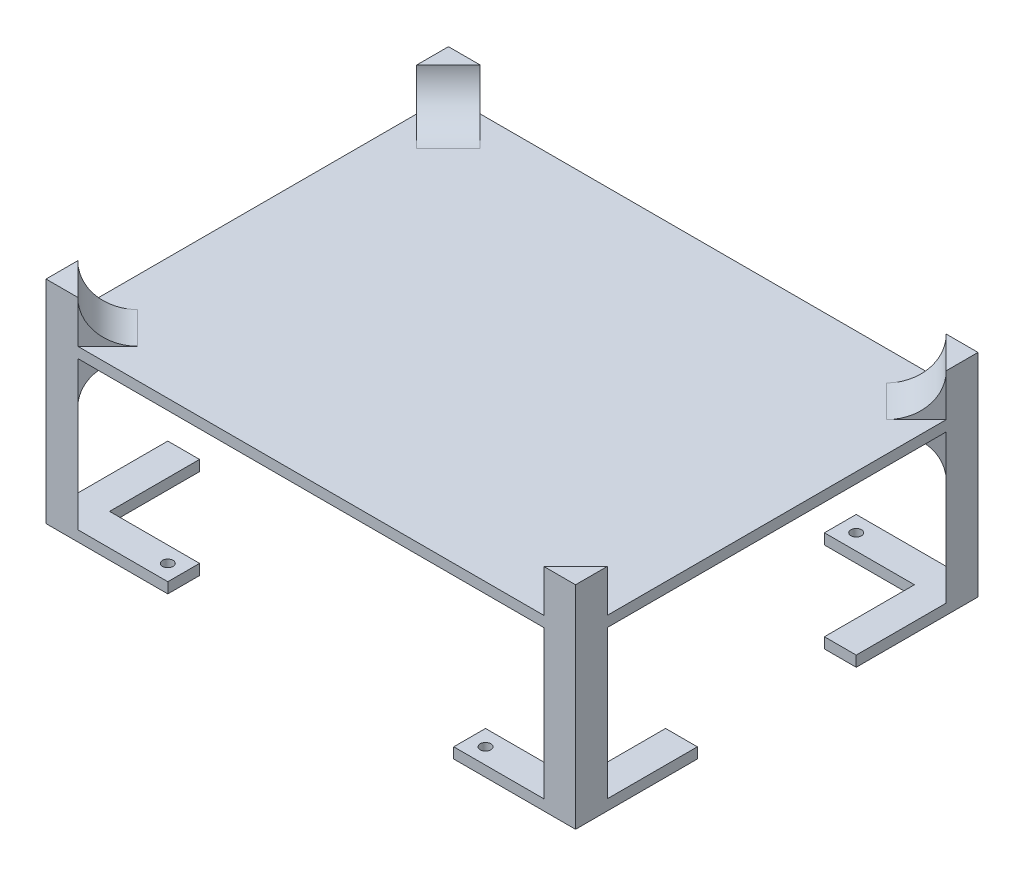
SolidWorks part; units mm, degrees
ref_plane "Front Plane" through (0, 0, 0) normal (0, 0, 1) x (1, 0, 0)
ref_plane "Top Plane" through (0, 0, 0) normal (0, 1, 0) x (1, 0, 0)
ref_plane "Right Plane" through (0, 0, 0) normal (1, 0, 0) x (0, 0, -1)
sketch "Sketch1" plane through (0, 0, 0) normal (0, 1, 0) x (1, 0, 0)
  line L0 (-125, 95) -> (-125, 80)
  line L5 (125, 95) -> (110, 95)
  line L6 (125, 80) -> (110, 95)
  line L7 (-125, 80) -> (-110, 95)
  line L8 (-125, 95) -> (-110, 95)
  line L11 (125, 95) -> (125, 80)
  line L12 (125, -95) -> (125, -80)
  line L13 (-125, -95) -> (-110, -95)
  line L14 (-125, -80) -> (-110, -95)
  line L15 (125, -80) -> (110, -95)
  line L16 (125, -95) -> (110, -95)
  line L17 (-125, -95) -> (-125, -80)
  point P0 (0, 0)
  dimension "D1" = 250
  dimension "D2" = 190
  dimension "D3" = 15
  dimension "D4" = 15
extrude "Boss-Extrude1" add sketch "Sketch1" along normal blind 100
sketch "Sketch3" plane through (125, 0, 0) normal (1, 0, 0) x (0, 0, -1)
  line L0 (-95, 80) -> (95, 80)
  line L1 (-95, 100) -> (-95, 0) construction
  line L2 (95, 100) -> (95, 0) construction
  line L3 (95, 80) -> (95, 75)
  line L4 (95, 75) -> (-95, 75)
  line L5 (-95, 100) -> (-80, 100) construction
  line L6 (-95, 80) -> (-95, 75)
  dimension "D1" = 5
  dimension "D2" = 20
extrude "Boss-Extrude3" add sketch "Sketch3" against normal through all
sketch "Sketch5" plane through (0, 0, 0) normal (0, -1, 0) x (1, 0, 0)
  line L18 (-110, 80) -> (-110, 37.5)
  line L22 (-110, 37.5) -> (-125, 37.5)
  line L24 (-125, 80) -> (-125, -80) construction
  line L60 (-110, 80) -> (-67.5, 80)
  line L61 (-67.5, 80) -> (-67.5, 95)
  line L62 (-110, 95) -> (110, 95) construction
  line L64 (-125, 37.5) -> (-125, 95)
  line L65 (-125, 95) -> (-67.5, 95)
  line L68 (125, 95) -> (67.5, 95)
  line L69 (125, 37.5) -> (125, 95)
  line L70 (67.5, 80) -> (67.5, 95)
  line L71 (110, 80) -> (67.5, 80)
  line L72 (110, 37.5) -> (125, 37.5)
  line L73 (110, 80) -> (110, 37.5)
  line L74 (110, -80) -> (110, -37.5)
  line L75 (110, -37.5) -> (125, -37.5)
  line L76 (110, -80) -> (67.5, -80)
  line L77 (67.5, -80) -> (67.5, -95)
  line L78 (125, -37.5) -> (125, -95)
  line L79 (125, -95) -> (67.5, -95)
  line L80 (-125, -95) -> (-67.5, -95)
  line L81 (-125, -37.5) -> (-125, -95)
  line L82 (-67.5, -80) -> (-67.5, -95)
  line L83 (-110, -80) -> (-67.5, -80)
  line L84 (-110, -37.5) -> (-125, -37.5)
  line L85 (-110, -80) -> (-110, -37.5)
  circle A0 centre (-75, 87.5) radius 2.5
  circle A3 centre (75, 87.5) radius 2.5
  circle A4 centre (75, -87.5) radius 2.5
  circle A7 centre (-75, -87.5) radius 2.5
  point P0 (0, 0)
  dimension "D5" = 5
  dimension "D1" = 57.5
  dimension "D2" = 57.5
  dimension "D3" = 15
  dimension "D4" = 15
  dimension "D7" = 7.5
extrude "Boss-Extrude6" add sketch "Sketch5" against normal blind 5
sketch "Sketch9" plane through (0, 100, 0) normal (0, 1, 0) x (1, 0, 0)
  line L0 (-110, 95) -> (-125, 80)
  line L1 (-125, 80) -> (-110.8579, 65.8579)
  line L2 (-110.8579, 65.8579) -> (-95.8579, 80.8579)
  line L3 (-110, 95) -> (-95.8579, 80.8579)
  line L6 (110, 95) -> (95.8579, 80.8579)
  line L7 (110.8579, 65.8579) -> (95.8579, 80.8579)
  line L8 (125, 80) -> (110.8579, 65.8579)
  line L9 (110, 95) -> (125, 80)
  line L10 (110, -95) -> (125, -80)
  line L11 (125, -80) -> (110.8579, -65.8579)
  line L12 (110.8579, -65.8579) -> (95.8579, -80.8579)
  line L13 (110, -95) -> (95.8579, -80.8579)
  line L14 (-110, -95) -> (-95.8579, -80.8579)
  line L15 (-110.8579, -65.8579) -> (-95.8579, -80.8579)
  line L16 (-125, -80) -> (-110.8579, -65.8579)
  line L17 (-110, -95) -> (-125, -80)
  dimension "D1" = 20
extrude "Boss-Extrude7" add sketch "Sketch9" against normal blind 45
sketch "Sketch11" plane through (7.5, 0, -7.5) normal (-0.7071, 0, 0.7071) x (0.7071, 0, 0.7071)
  line L0 (124.9569, 80) -> (124.9569, 100)
  line L1 (124.9569, 100) -> (144.9569, 100)
  line L2 (124.9569, 75) -> (124.9569, 55)
  line L3 (124.9569, 55) -> (144.9569, 55)
  arc A0 (124.9569, 80) -> (144.9569, 100) centre (124.9569, 100) ccw
  arc A1 (124.9569, 75) -> (144.9569, 55) centre (124.9569, 55) cw
extrude "Cut-Extrude2" cut sketch "Sketch11" against normal up to next contours L0 L1 A0 | L2 L3 A1
sketch "Sketch12" plane through (22.5, 0, 22.5) normal (0.7071, 0, 0.7071) x (0.7071, 0, -0.7071)
  line L0 (144.9569, 100) -> (124.9569, 100)
  line L1 (124.9569, 100) -> (124.9569, 80)
  line L2 (144.9569, 55) -> (124.9569, 55)
  line L3 (124.9569, 55) -> (124.9569, 75)
  arc A0 (144.9569, 100) -> (124.9569, 80) centre (124.9569, 100) cw
  arc A1 (144.9569, 55) -> (124.9569, 75) centre (124.9569, 55) ccw
extrude "Cut-Extrude3" cut sketch "Sketch12" against normal up to next contours L0 L1 A0 | L2 L3 A1
sketch "Sketch13" plane through (-7.5, 0, -7.5) normal (0.7071, 0, 0.7071) x (0.7071, 0, -0.7071)
  line L0 (-144.9569, 100) -> (-124.9569, 100)
  line L1 (-124.9569, 100) -> (-124.9569, 80)
  line L2 (-124.9569, 75) -> (-124.9569, 55)
  line L3 (-124.9569, 55) -> (-144.9569, 55)
  arc A0 (-144.9569, 100) -> (-124.9569, 80) centre (-124.9569, 100) ccw
  arc A1 (-144.9569, 55) -> (-124.9569, 75) centre (-124.9569, 55) cw
extrude "Cut-Extrude4" cut sketch "Sketch13" against normal up to next contours L0 L1 A0 | L3 A1 L2
sketch "Sketch14" plane through (-22.5, 0, 22.5) normal (-0.7071, 0, 0.7071) x (0.7071, 0, 0.7071)
  line L0 (-144.9569, 100) -> (-124.9569, 100)
  line L1 (-124.9569, 100) -> (-124.9569, 80)
  line L2 (-144.9569, 55) -> (-124.9569, 55)
  line L3 (-124.9569, 55) -> (-124.9569, 75)
  arc A0 (-144.9569, 100) -> (-124.9569, 80) centre (-124.9569, 100) ccw
  arc A1 (-124.9569, 75) -> (-144.9569, 55) centre (-124.9569, 55) ccw
extrude "Cut-Extrude5" cut sketch "Sketch14" against normal up to next contours L0 L1 A0 | L3 A1 L2
